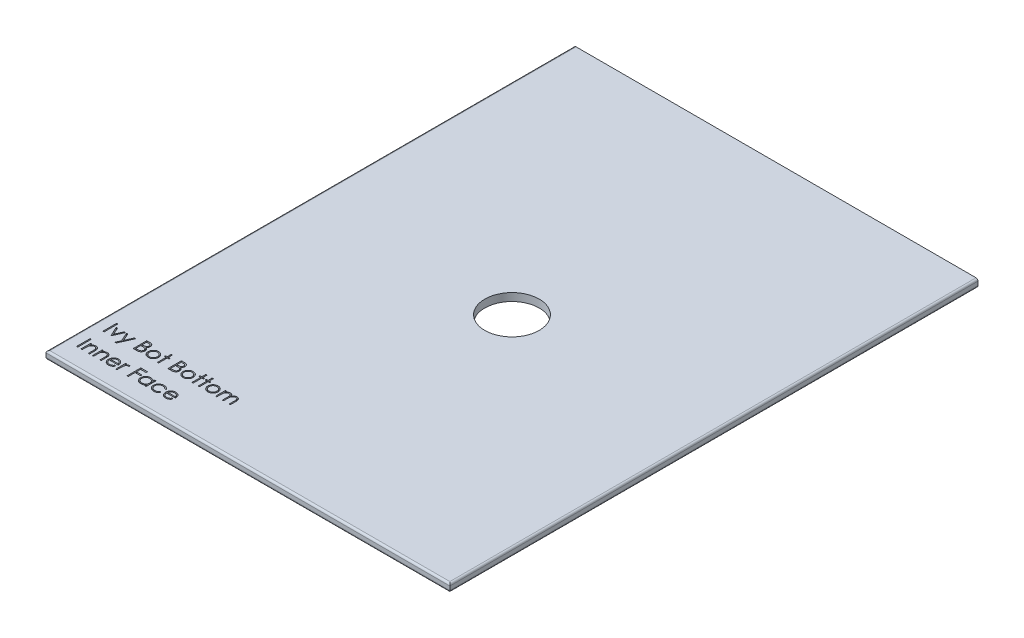
SolidWorks part; units mm, degrees
ref_plane "Front Plane" through (0, 0, 0) normal (0, 0, 1) x (1, 0, 0)
ref_plane "Top Plane" through (0, 0, 0) normal (0, 1, 0) x (1, 0, 0)
ref_plane "Right Plane" through (0, 0, 0) normal (1, 0, 0) x (0, 0, -1)
sketch "Sketch1" plane through (0, 0, 0) normal (0, 1, 0) x (1, 0, 0)
  line L1 (-52, 68) -> (52, 68)
  line L2 (-52, 68) -> (-52, -68)
  line L3 (-52, -68) -> (52, -68)
  line L4 (52, 68) -> (52, -68)
  point P4 (0, -68)
  point P6 (-52, 0)
  dimension "D1" = 104
  dimension "D2" = 136
extrude "Boss-Extrude1" add sketch "Sketch1" along normal blind 2 contours L1 L4 L3 L2
sketch "Sketch6" plane through (0, 2, 0) normal (0, 1, 0) x (1, 0, 0)
  circle A0 centre (0, 0) radius 7
  dimension "D1" = 14
extrude "Cut-Extrude1" cut sketch "Sketch6" against normal through all contours A0
fillet "Fillet1" radius 0.5 7 edges at (-52, 0, 0) (0, 0, -68) (0, 0, 68) (52, 0, 0) (52, 2, 0) (-52, 2, 0) (0, 2, 68)
sketch "Sketch9" plane through (0, 2, 0) normal (0, 1, 0) x (1, 0, 0)
  text T0 "Ivy Bot Bottom\r\nInner Face"
extrude "Cut-Extrude4" cut sketch "Sketch9" against normal blind 1
sketch "Sketch10" plane through (0, 0, 0) normal (0, -1, 0) x (1, 0, 0)
  line L0 (-12.9733, 25) -> (12.9733, 25) construction
  line L1 (-12.9733, -25) -> (12.9733, -25) construction
  text T0 "3               1"
  text T1 " 2               4"
  point P8 (0, 25)
  point P12 (0, -25)
  dimension "D1" = 25
  dimension "D2" = 25
extrude "Cut-Extrude5" cut sketch "Sketch10" against normal blind 1
sketch "Sketch11" plane through (0, 0, 0) normal (0, -1, 0) x (1, 0, 0)
  line L0 (0, 67.5) -> (0, -67.5) construction
  line L1 (51.5, 67.5) -> (-51.5, 67.5) construction
  line L2 (-51.5, -67.5) -> (51.5, -67.5) construction
  line L3 (-51.5, 0) -> (51.5, 0) construction
  line L4 (51.5, -67.5) -> (51.5, 67.5) construction
  line L5 (40, 0) -> (-40, 0) construction
  circle A0 centre (-40, 0) radius 2.5
  circle A1 centre (40, 0) radius 2.5
  point P9 (0, 0)
  point P10 (37.1653, 0)
  point P13 (0, 0)
  point P17 (0, 0)
extrude "Boss-Extrude2" add sketch "Sketch11" along normal blind 10
fillet "Fillet4" radius 2 2 edges at (40, -10, 2.5) (-40, -10, -2.5)
